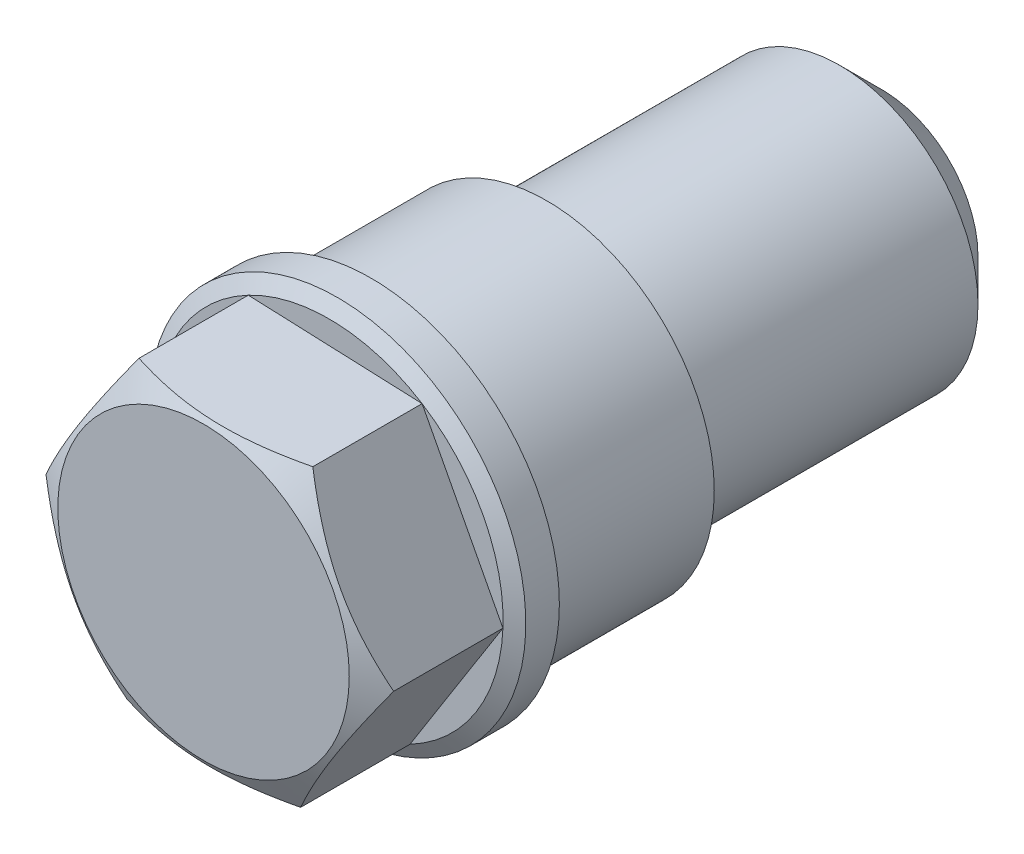
SolidWorks part; units mm, degrees
ref_plane "Спереди" through (0, 0, 0) normal (0, 0, 1) x (1, 0, 0)
ref_plane "Сверху" through (0, 0, 0) normal (0, 1, 0) x (1, 0, 0)
ref_plane "Справа" through (0, 0, 0) normal (1, 0, 0) x (0, 0, -1)
sketch "Эскиз1" plane through (0, 0, 0) normal (0, 0, 1) x (1, 0, 0)
  circle A0 centre (0, 0) radius 3.3
extrude "Бобышка-Вытянуть1" add sketch "Эскиз1" along normal blind 8
sketch "Эскиз2" plane through (0, 0, 8) normal (0, 0, 1) x (1, 0, 0)
  circle A0 centre (0, 0) radius 4
extrude "Бобышка-Вытянуть2" add sketch "Эскиз2" along normal blind 4.2 contours A0
sketch "Эскиз3" plane through (0, 0, 12.2) normal (0, 0, 1) x (1, 0, 0)
  circle A0 centre (0, 0) radius 4.5
extrude "Бобышка-Вытянуть3" add sketch "Эскиз3" along normal blind 1
sketch "Эскиз4" plane through (0, 0, 13.2) normal (0, 0, 1) x (1, 0, 0)
  circle A0 centre (0, 0) radius 4.1556
extrude "Вырез-Вытянуть1" cut sketch "Эскиз4" against normal blind 1 draft 60 flip side to cut
sketch "Эскиз5" plane through (0, 0, 13.2) normal (0, 0, 1) x (1, 0, 0)
  line L1 (-4.1522, 0.1675) -> (-2.2212, -3.5121)
  line L2 (-2.2212, -3.5121) -> (1.931, -3.6797)
  line L3 (1.931, -3.6797) -> (4.1522, -0.1675)
  line L4 (4.1522, -0.1675) -> (2.2212, 3.5121)
  line L5 (2.2212, 3.5121) -> (-1.931, 3.6797)
  line L6 (-1.931, 3.6797) -> (-4.1522, 0.1675)
  circle A0 centre (0, 0) radius 3.5988 construction
extrude "Бобышка-Вытянуть4" add sketch "Эскиз5" along normal blind 3
sketch "Эскиз6" plane through (0, 0, 16.2) normal (0, 0, 1) x (1, 0, 0)
  circle A0 centre (0, 0) radius 3.4811
extrude "Вырез-Вытянуть2" cut sketch "Эскиз6" against normal blind 3 draft 60 flip side to cut
chamfer "Фаска1" distance 1 angle 45 1 edges at (3.3, 0, 0)
